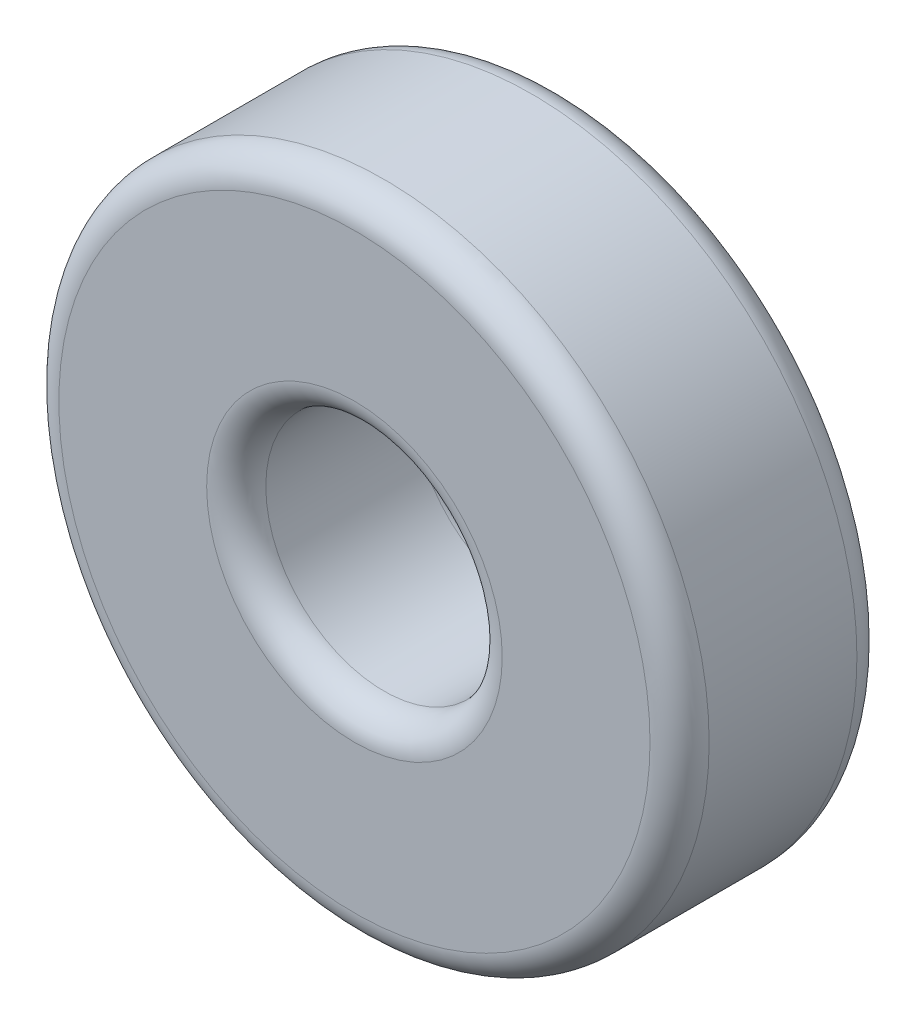
SolidWorks part; units mm, degrees
ref_plane "Front Plane" through (0, 0, 0) normal (1, 0, 0) x (0, 1, 0)
ref_plane "Top Plane" through (0, 0, 0) normal (0, 0, 1) x (0, 1, 0)
ref_plane "Right Plane" through (0, 0, 0) normal (0, 1, 0) x (-1, 0, 0)
sketch "Sketch2" plane through (0, 0, 0) normal (0, 0, 1) x (0, 1, 0)
  circle A0 centre (0, 0) radius 11
  circle A1 centre (0, 0) radius 4
  dimension "D1" = 22
  dimension "D2" = 8
extrude "Boss-Extrude1" add sketch "Sketch2" along normal blind 7
fillet "Fillet1" radius 1 4 edges at (4, 0, 0) (11, 0, 0) (4, 0, 7) (11, 0, 7)
